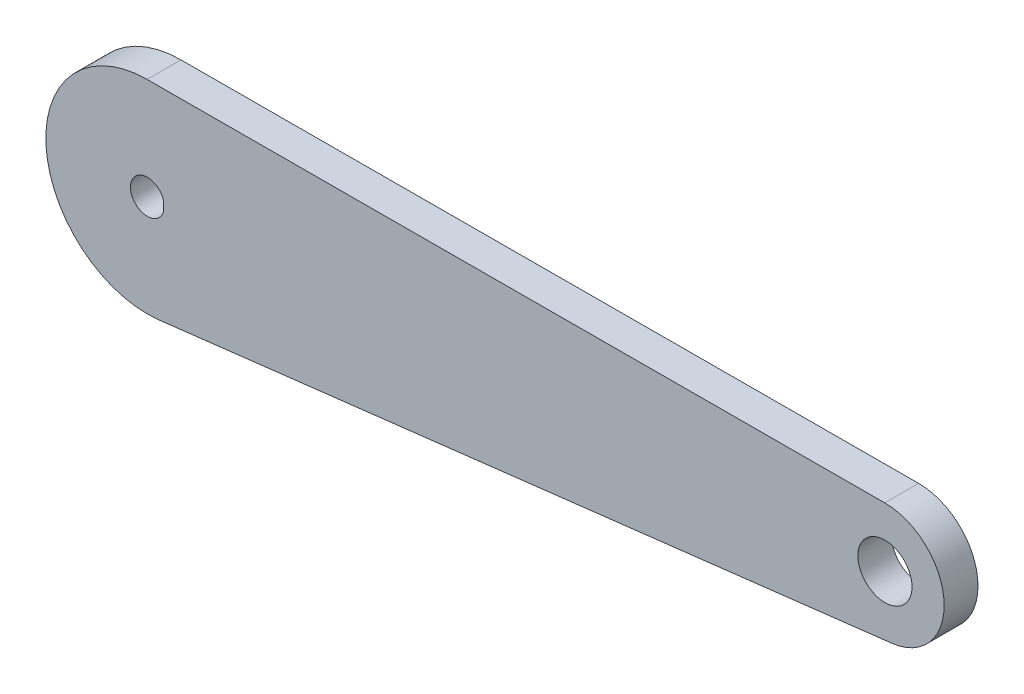
SolidWorks part; units mm, degrees
ref_plane "前视基准面" through (0, 0, 0) normal (0, 0, 1) x (1, 0, 0)
ref_plane "上视基准面" through (0, 0, 0) normal (0, 1, 0) x (1, 0, 0)
ref_plane "右视基准面" through (0, 0, 0) normal (1, 0, 0) x (0, 0, -1)
other "Configuration Table"
sketch "草图2" plane through (0, 0, 0) normal (0, 0, 1) x (1, 0, 0)
  line L0 (-0.0427, 14.9999) -> (108.9573, 15.3103)
  line L1 (1.757, -14.8967) -> (110.0071, -2.1295)
  circle A0 centre (0, 0) radius 15
  circle A1 centre (108.9822, 6.5603) radius 8.75
  point P9 (0, 0)
  dimension "D1" = 30
  dimension "D2" = 17.5
  dimension "D3" = 109
  dimension "D4" = 109
  dimension "D5" = 109.0004
extrude "凸台-拉伸1" add sketch "草图2" along normal blind 5 contours A0 | A1 L0 A0 L1 | A1
sketch "草图3" plane through (0, 0, 5) normal (0, 0, 1) x (1, 0, 0)
  line L0 (0, 0) -> (2.4, 0)
  line L1 (2.4, 0) -> (2.4, 0.7)
  line L2 (2.4, 0.7) -> (2.4, -0.7)
  circle A0 centre (108.9822, 6.5603) radius 4
  circle A1 centre (0, 0) radius 2.5
  point P6 (0, 0)
  point P10 (2.4143, -0.649)
  dimension "D1" = 8
  dimension "D2" = 5
  dimension "D3" = 2.4
extrude "切除-拉伸1" cut sketch "草图3" against normal blind 5
